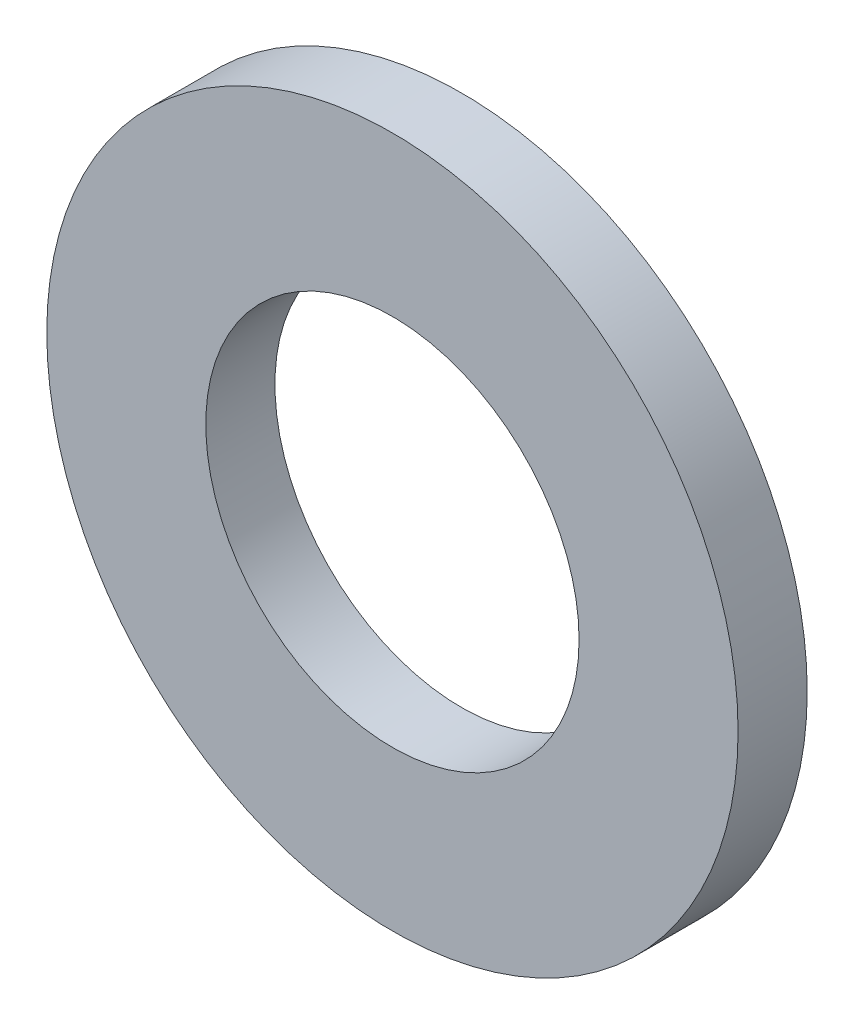
SolidWorks part; units mm, degrees
ref_plane "Front Plane" through (0, 0, 0) normal (0, 0, 1) x (1, 0, 0)
ref_plane "Top Plane" through (0, 0, 0) normal (0, 1, 0) x (1, 0, 0)
ref_plane "Right Plane" through (0, 0, 0) normal (1, 0, 0) x (0, 0, -1)
sketch "Washer_profile" plane through (0, 0, 0) normal (0, 0, 1) x (1, 0, 0)
  circle A0 centre (0, 0) radius 2.5
  circle A1 centre (0, 0) radius 1.35
  dimension "D1" = 5
  dimension "D2" = 2.7
extrude "Washer" add sketch "Washer_profile" along normal blind 0.5
